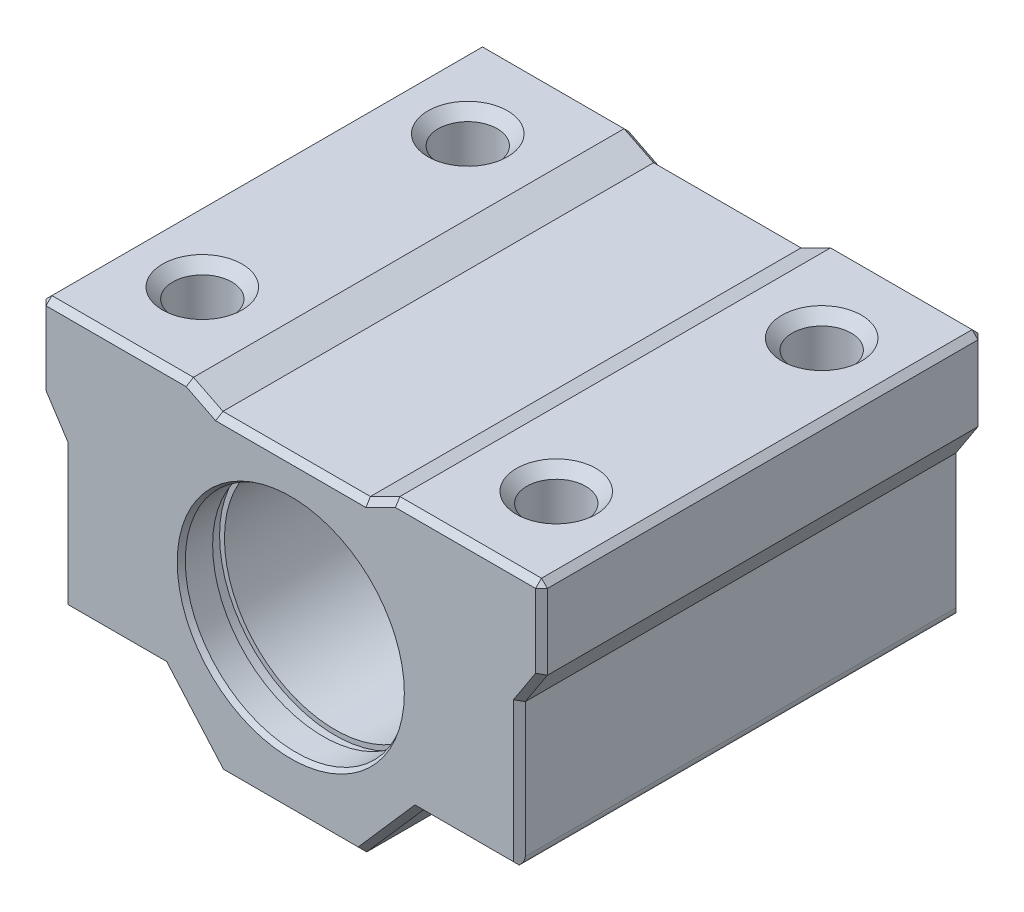
SolidWorks part; units mm, degrees
material "1060 Alloy"
ref_plane "Front Plane" through (0, 0, 0) normal (0, 0, 1) x (1, 0, 0)
ref_plane "Top Plane" through (0, 0, 0) normal (0, 1, 0) x (1, 0, 0)
ref_plane "Right Plane" through (0, 0, 0) normal (1, 0, 0) x (0, 0, -1)
sketch "Sketch1" plane through (0, 0, 0) normal (0, 0, 1) x (1, 0, 0)
  line L0 (0, 0) -> (0, -120.6263) construction
  line L1 (-5, -1) -> (5, -1)
  line L2 (5, -1) -> (7, 0)
  line L3 (7, 0) -> (17, 0)
  line L4 (17, 0) -> (17, -5.5)
  line L5 (17, -5.5) -> (15.5, -7.8)
  line L6 (15.5, -7.8) -> (15.5, -17.6)
  line L7 (15.5, -17.6) -> (8.6, -17.6)
  line L8 (8.6, -17.6) -> (4.75, -22)
  line L9 (4.75, -22) -> (-4.75, -22)
  line L10 (-15.5, -7.8) -> (-15.5, -17.6)
  line L11 (-17, -5.5) -> (-15.5, -7.8)
  line L12 (-17, 0) -> (-17, -5.5)
  line L13 (-7, 0) -> (-17, 0)
  line L14 (-5, -1) -> (-7, 0)
  line L15 (-15.5, -17.6) -> (-8.6, -17.6)
  line L16 (-8.6, -17.6) -> (-4.75, -22)
  circle A0 centre (0, -11) radius 7.5
  point P19 (0, -1)
  point P21 (0, -22)
  dimension "D4" = 15
  dimension "D1" = 5.5
  dimension "D2" = 1
  dimension "D3" = 1.5
  dimension "D5" = 34
  dimension "D6" = 22
  dimension "D7" = 7.8
  dimension "D8" = 2
  dimension "D9" = 17.6
  dimension "D10" = 11
  dimension "D11" = 10
  dimension "D12" = 9.5
  dimension "D13" = 17.2
extrude "Boss-Extrude1" add sketch "Sketch1" along normal mid plane 30
chamfer "Chaflàn0" distance 0.2 angle 60 2 edges at (7.5, -11, -15) (7.5, -11, 15)
sketch "Croquis1" plane through (0, 0, 0) normal (0, 1, 0) x (1, 0, 0)
  line L0 (0, 0) -> (-17, 0) construction
  line L1 (-17, -15) -> (-17, 15) construction
  line L2 (-12, 15) -> (-12, -15) construction
  line L3 (-7, 15) -> (-17, 15) construction
  line L4 (-7, -15) -> (-17, -15) construction
  line L5 (12, 15) -> (12, -15) construction
  line L6 (17, 15) -> (7, 15) construction
  line L7 (17, -15) -> (7, -15) construction
  circle A0 centre (-12, 9) radius 2
  circle A1 centre (12, 9) radius 2
  circle A2 centre (-12, -9) radius 2
  circle A3 centre (12, -9) radius 2
  dimension "D1" = 4
  dimension "D2" = 4
  dimension "D3" = 4
  dimension "D4" = 4
  dimension "D5" = 18
  dimension "D6" = 9
  dimension "D7" = 9
  dimension "D8" = 9
extrude "Cortar-Extruir1" cut sketch "Croquis1" against normal blind 20
chamfer "Chaflán1" distance 0.7 angle 45 8 edges at (-14, -17.6, 9) (-14, -17.6, -9) (10, -17.6, 9) (10, -17.6, -9) (10, 0, 9) (-14, 0, 9) (10, 0, -9) (-14, 0, -9)
chamfer "Chaflán2" distance 0.4 angle 45 34 edges at (12, 0, 15) (17, -2.75, 15) (16.25, -6.65, 15) (15.5, -12.7, 15) (12.05, -17.6, 15) (6.675, -19.8, 15) (0, -22, 15) (-6.675, -19.8, 15) (-12.05, -17.6, 15) (-15.5, -12.7, 15) (-16.25, -6.65, 15) (-17, -2.75, 15) (-12, 0, 15) (-6, -0.5, 15) (0, -1, 15) (6, -0.5, 15) (0, -1, -15) (-6, -0.5, -15) (-12, 0, -15) (-17, -2.75, -15) (-16.25, -6.65, -15) (-15.5, -12.7, -15) (-12.05, -17.6, -15) (-6.675, -19.8, -15) (0, -22, -15) (6.675, -19.8, -15) (12.05, -17.6, -15) (15.5, -12.7, -15) (16.25, -6.65, -15) (17, -2.75, -15) (12, 0, -15) (6, -0.5, -15) (17, 0, 0) (-17, 0, 0)
fillet "Redondeo1" radius 0.7 2 edges at (15.5, -17.6, 0) (-15.5, -17.6, 0)
ref_plane "Plane1" through (0, 0, 12.8) normal (0, 0, 1) x (1, 0, 0)
sketch "Sketch2" plane through (0, 0, 12.8) normal (0, 0, 1) x (1, 0, 0)
  circle A0 centre (0, -11) radius 7.83
extrude "Cut-Extrude1" cut sketch "Sketch2" against normal blind 0.8
mirror "Mirror1" about plane through (0, 0, 0) normal (0, 0, 1) of "Cut-Extrude1"
